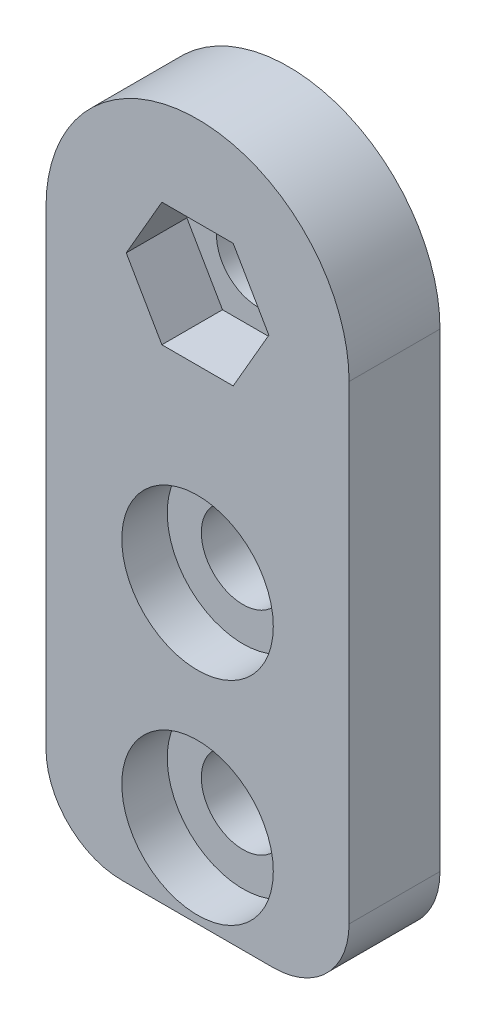
SolidWorks part; units mm, degrees
ref_plane "Спереди" through (0, 0, 0) normal (0, 0, 1) x (1, 0, 0)
ref_plane "Сверху" through (0, 0, 0) normal (0, 1, 0) x (1, 0, 0)
ref_plane "Справа" through (0, 0, 0) normal (1, 0, 0) x (0, 0, -1)
sketch "Эскиз2" plane through (0, 0, 0) normal (0, 0, 1) x (1, 0, 0)
  line L0 (0, -18) -> (0, 7) construction
  line L2 (10, 18) -> (10, -18)
  line L3 (10, -18) -> (-10, -18)
  line L4 (-10, 18) -> (-10, -18)
  line L5 (10, 18) -> (-10, -18) construction
  line L6 (10, -18) -> (-10, 18) construction
  line L7 (0, -5.5) -> (-10, -5.5) construction
  circle A0 centre (0, 1.5) radius 2.75
  circle A1 centre (0, -12.5) radius 2.75
  arc A2 (-10, 18) -> (10, 18) centre (0, 18) cw
  circle A3 centre (0, 18) radius 2.75
  point P0 (0, 0)
  dimension "D5" = 5.5
  dimension "D6" = 5.5
  dimension "D1" = 36
  dimension "D2" = 20
  dimension "D3" = 25
  dimension "D4" = 14
extrude "Бобышка-Вытянуть1" add sketch "Эскиз2" along normal blind 6
sketch "Эскиз3" plane through (0, 0, 6) normal (0, 0, 1) x (1, 0, 0)
  circle A0 centre (0, 1.5) radius 5
  circle A1 centre (0, -12.5) radius 5
  dimension "D1" = 10
  dimension "D2" = 10
extrude "Вырез-Вытянуть1" cut sketch "Эскиз3" against normal blind 3
fillet "Скругление1" radius 5 2 edges at (-10, -18, 3) (10, -18, 3)
sketch "Эскиз4" plane through (0, 0, 6) normal (0, 0, 1) x (1, 0, 0)
  line L1 (2.3527, 13.925) -> (4.7054, 18)
  line L2 (4.7054, 18) -> (2.3527, 22.075)
  line L3 (2.3527, 22.075) -> (-2.3527, 22.075)
  line L4 (-2.3527, 22.075) -> (-4.7054, 18)
  line L5 (-4.7054, 18) -> (-2.3527, 13.925)
  line L6 (-2.3527, 13.925) -> (2.3527, 13.925)
  circle A1 centre (0, 18) radius 4.075 construction
  dimension "D1" = 8.15
extrude "Вырез-Вытянуть2" cut sketch "Эскиз4" against normal blind 4
equation "\"print_offset\"= 0.5"
equation "\"screw_m5_d\"= 5"
equation "\"screw_m5_hh_d\"= 9.5"
equation "\"nut_m5_d\"= 7.9"
equation "\"nut_m5_h\"= 3.9"
equation "\"tube_d\"= 16"
equation "\"tube_tape_d\"= 3"
equation "\"tube_tape_h\"= 11"
equation "\"D5@Эскиз2\"=\"screw_m5_d\"+\"print_offset\""
equation "\"D6@Эскиз2\"=\"D5@Эскиз2\""
equation "\"D1@Эскиз3\"=\"screw_m5_hh_d\"+\"print_offset\""
equation "\"D2@Эскиз3\"=\"D1@Эскиз3\""
equation "\"D1@Эскиз4\"=\"nut_m5_d\"+\"print_offset\"/2"
